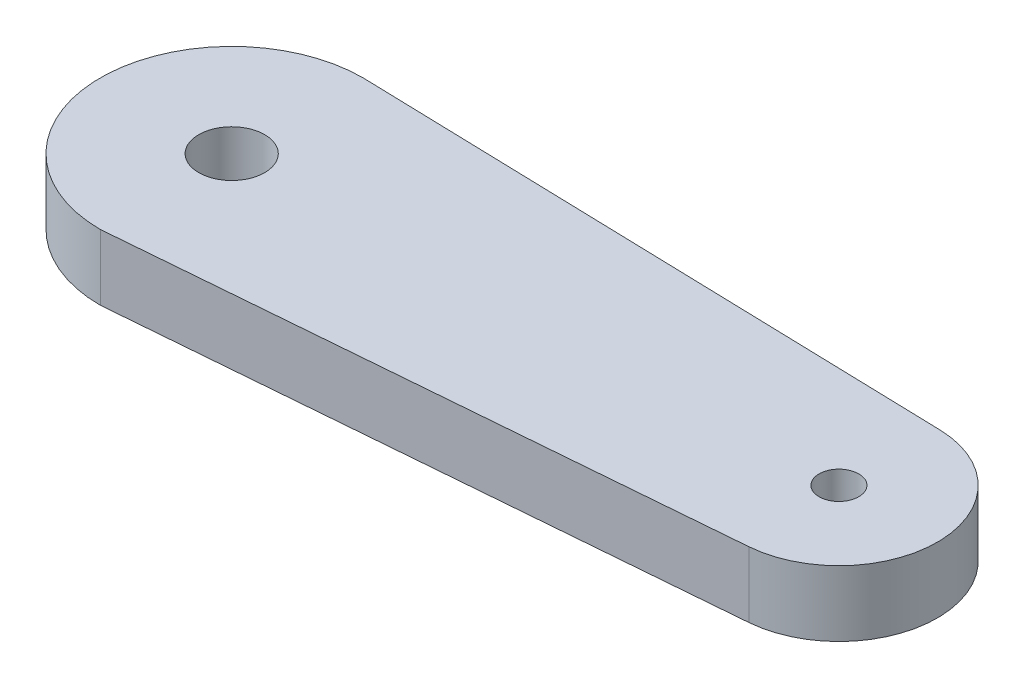
SolidWorks part; units mm, degrees
ref_plane "Front Plane" through (0, 0, 0) normal (0, 0, 1) x (1, 0, 0)
ref_plane "Top Plane" through (0, 0, 0) normal (0, 1, 0) x (1, 0, 0)
ref_plane "Right Plane" through (0, 0, 0) normal (1, 0, 0) x (0, 0, -1)
sketch "Sketch1" plane through (0, 0, 0) normal (0, 1, 0) x (1, 0, 0)
  line L0 (0, 10) -> (45.1912, 8.7436)
  line L1 (0, -10) -> (45.601, -6.2279)
  circle A0 centre (0, 0) radius 10
  circle A1 centre (44.9827, 1.2465) radius 7.5
  dimension "D2" = 20
  dimension "D3" = 15
  dimension "D1" = 45
extrude "Boss-Extrude1" add sketch "Sketch1" along normal blind 5 contours L1 A0 L0 | A1 L0 A0 L1 | A1 L1
sketch "Sketch2" plane through (0, 5, 0) normal (0, 1, 0) x (1, 0, 0)
  circle A0 centre (0, 0) radius 2.51
  circle A1 centre (44.9827, 1.2465) radius 1.51
  dimension "D1" = 5.02
  dimension "D2" = 3.02
extrude "Cut-Extrude1" cut sketch "Sketch2" against normal up to next
